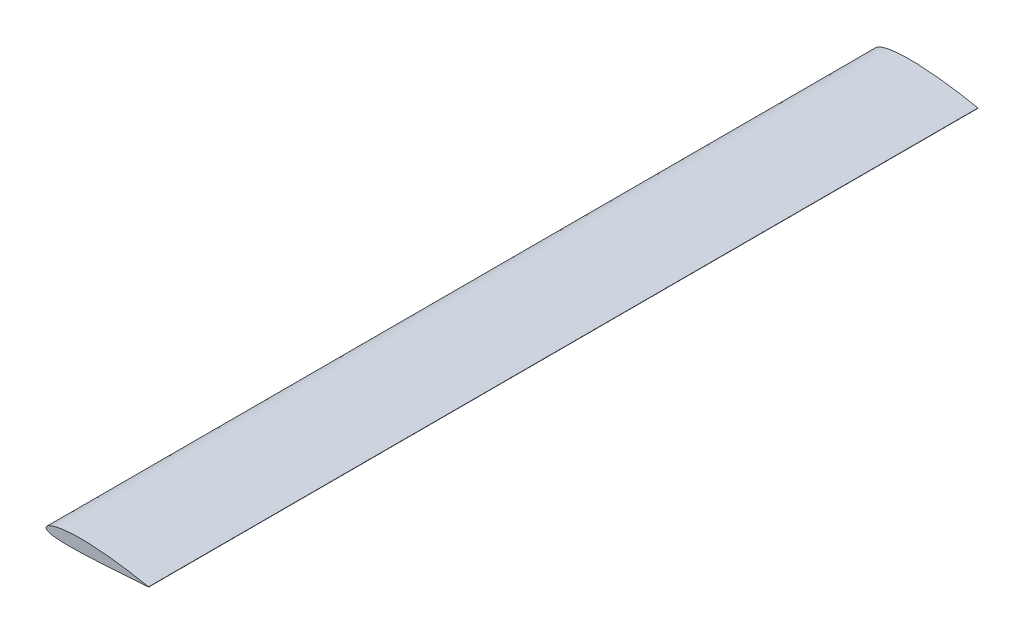
SolidWorks part; units mm, degrees
ref_plane "Front Plane" through (0, 0, 0) normal (0, 0, 1) x (1, 0, 0)
ref_plane "Top Plane" through (0, 0, 0) normal (0, 1, 0) x (1, 0, 0)
ref_plane "Right Plane" through (0, 0, 0) normal (1, 0, 0) x (0, 0, -1)
curve "Curve1"
  spline degree 3 poles (1, 0.0013, 0) (0.9833, 0.0047, 0) (0.9501, 0.0115, 0) (0.8835, 0.024, 0) (0.8002, 0.0379, 0) (0.7002, 0.0522, 0) (0.6002, 0.0641, 0) (0.5001, 0.0729, 0) (0.4001, 0.0788, 0) (0.3166, 0.0798, 0) (0.2499, 0.077, 0) (0.1999, 0.073, 0) (0.1498, 0.0666, 0) (0.108, 0.0587, 0) (0.0748, 0.0498, 0) (0.0496, 0.0416, 0) (0.0282, 0.0322, 0) (0.0098, 0.0207, 0) (-0.0063, 0.0009, 0) (0.0104, -0.0165, 0) (0.0285, -0.0245, 0) (0.0497, -0.0305, 0) (0.0749, -0.0348, 0) (0.1083, -0.0385, 0) (0.1499, -0.0414, 0) (0.2, -0.0425, 0) (0.25, -0.0424, 0) (0.3167, -0.0409, 0) (0.4, -0.0382, 0) (0.5, -0.0336, 0) (0.6, -0.0276, 0) (0.7, -0.0214, 0) (0.8, -0.0151, 0) (0.8833, -0.0093, 0) (0.95, -0.0048, 0) (0.9833, -0.0025, 0) (1, -0.0013, 0) knots 0 0 0 0 0.025012 0.049959 0.099673 0.149206 0.198581 0.247805 0.296917 0.345953 0.370492 0.395091 0.419815 0.444799 0.45749 0.470406 0.483879 0.491264 0.503459 0.513609 0.520451 0.533235 0.545691 0.558032 0.582609 0.607135 0.631652 0.656174 0.705234 0.75432 0.803437 0.852566 0.901701 0.950849 0.975423 1 1 1 1
sketch "Sketch3" plane through (0, 0, 0) normal (0, 0, 1) x (1, 0, 0)
  line L0 (350, 0.455) -> (350, -0.455)
  spline S1 degree 3 poles (350, 0.455) (344.1699, 1.6497) (332.525, 4.0359) (309.2153, 8.4065) (280.0623, 13.2492) (245.0557, 18.2612) (210.0548, 22.4411) (175.0388, 25.5017) (140.0307, 27.5743) (110.8224, 27.9251) (87.4788, 26.9587) (69.9568, 25.5427) (52.4127, 23.3002) (37.8116, 20.5389) (26.1713, 17.4148) (17.3463, 14.5746) (9.8694, 11.2652) (3.4198, 7.2531) (-2.2044, 0.3146) (3.6377, -5.7842) (9.9666, -8.5659) (17.4106, -10.6788) (26.2066, -12.1938) (37.8934, -13.4866) (52.4815, -14.4817) (69.9979, -14.8807) (87.5019, -14.8251) (110.8374, -14.31) (140.0095, -13.3831) (175.0117, -11.7701) (210.0037, -9.6735) (245.0017, -7.4943) (280.0056, -5.2884) (309.166, -3.2569) (332.5015, -1.6899) (344.1669, -0.8666) (350, -0.455) knots 0 0 0 0 0.025012 0.049959 0.099673 0.149206 0.198581 0.247805 0.296917 0.345953 0.370492 0.395091 0.419815 0.444799 0.45749 0.470406 0.483879 0.491264 0.503459 0.513609 0.520451 0.533235 0.545691 0.558032 0.582609 0.607135 0.631652 0.656174 0.705234 0.75432 0.803437 0.852566 0.901701 0.950849 0.975423 1 1 1 1
extrude "Boss-Extrude2" add sketch "Sketch3" along normal blind 1415
mirror "Mirror1" about plane through (0.3255, 2.2995, 0) normal (0, 0, -1) of "Boss-Extrude2"
